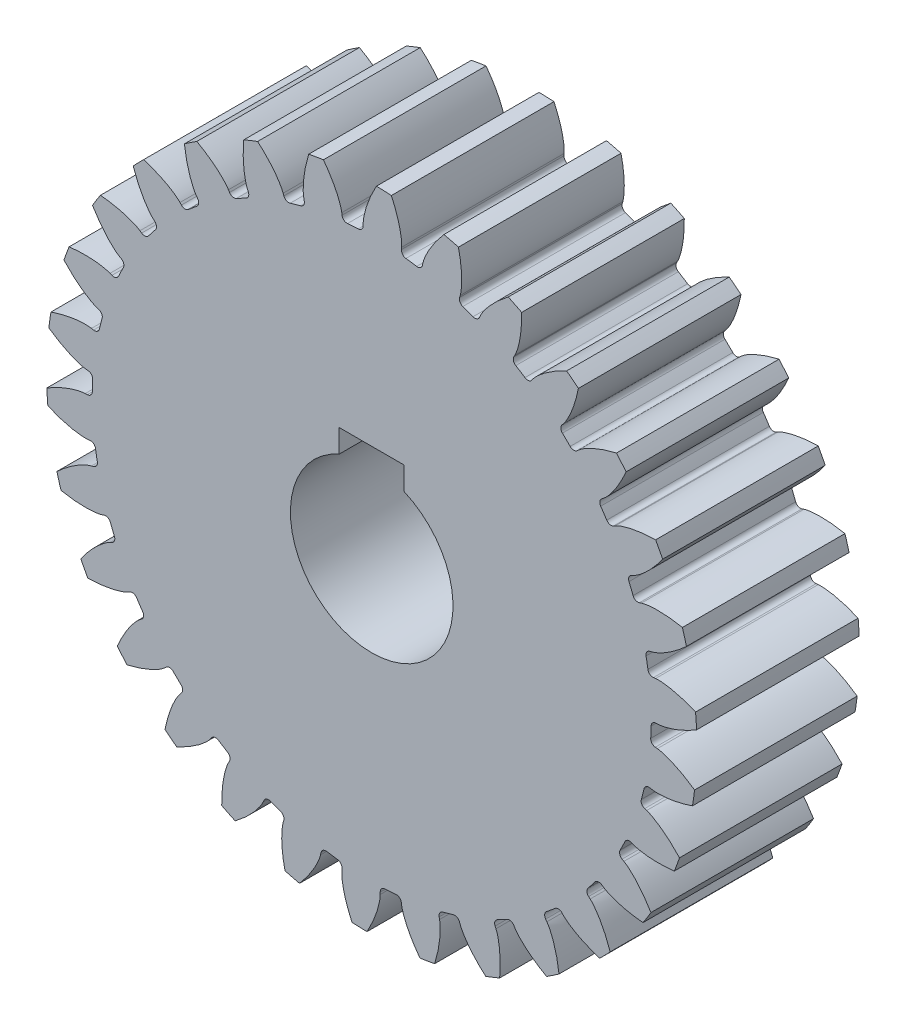
SolidWorks part; units mm, degrees
material "普通碳钢"
ref_plane "前视基准面" through (0, 0, 0) normal (0, 0, 1) x (1, 0, 0)
ref_plane "上视基准面" through (0, 0, 0) normal (0, 1, 0) x (1, 0, 0)
ref_plane "右视基准面" through (0, 0, 0) normal (1, 0, 0) x (0, 0, -1)
sketch "草图1" plane through (0, 0, 0) normal (0, 0, 1) x (1, 0, 0)
  circle A0 centre (0, 0) radius 40
  circle A1 centre (0, 0) radius 35.2385 construction
  spline S0 degree 4 poles (35.2385, 0) (35.2645, 0.0006) (35.3375, 0.0038) (35.4753, 0.0167) (35.6991, 0.0472) (35.9825, 0.1001) (36.3462, 0.1844) (36.7705, 0.304) (37.2317, 0.4565) (37.7271, 0.6449) (38.2153, 0.8527) (38.6956, 1.0778) (39.1683, 1.3186) (39.7325, 1.6284) (40.3986, 2.0272) (41.1576, 2.5279) (41.9984, 3.1428) (42.8253, 3.8079) (43.6227, 4.5077) (44.3913, 5.2397) (45.0381, 5.9049) (45.5755, 6.4929) (46.0974, 7.0914) (46.523, 7.6039) (46.9323, 8.1186) (47.3374, 8.6535) (47.6437, 9.0696) (47.9643, 9.5236) (48.2398, 9.9227) (48.6343, 10.5199) (48.8641, 10.8815) (49.2267, 11.4659) (49.3796, 11.7307) (49.5219, 11.9693) (49.5614, 12.0402) (49.5915, 12.0919) (49.6078, 12.1198) knots 0 0 0 0 0 0.005377 0.015084 0.028532 0.04661 0.064855 0.092111 0.119476 0.146842 0.174209 0.201575 0.228941 0.256307 0.307035 0.361767 0.4165 0.471232 0.525964 0.580697 0.635429 0.662795 0.690161 0.744894 0.77226 0.799626 0.826992 0.854358 0.881725 0.909091 0.954545 0.977273 0.988636 0.994318 1 1 1 1 1 construction
  spline S1 degree 4 poles (35.2385, 0) (35.2645, 0.0006) (35.3375, 0.0038) (35.4753, 0.0167) (35.6991, 0.0472) (35.9825, 0.1001) (36.3462, 0.1844) (36.7705, 0.304) (37.2317, 0.4565) (37.7271, 0.6449) (38.2153, 0.8527) (38.6956, 1.0778) (39.1683, 1.3186) (39.7325, 1.6284) (40.3986, 2.0272) (41.1576, 2.5279) (41.9984, 3.1428) (42.8253, 3.8079) (43.6227, 4.5077) (44.3913, 5.2397) (45.0381, 5.9049) (45.5755, 6.4929) (46.0974, 7.0914) (46.523, 7.6039) (46.9323, 8.1186) (47.3374, 8.6535) (47.6437, 9.0696) (47.9643, 9.5236) (48.2398, 9.9227) (48.4937, 10.3071) (48.6265, 10.5113) (48.6916, 10.6127) knots 0 0 0 0 0 0.005377 0.015084 0.028532 0.04661 0.064855 0.092111 0.119476 0.146842 0.174209 0.201575 0.228941 0.256307 0.307035 0.361767 0.4165 0.471232 0.525964 0.580697 0.635429 0.662795 0.690161 0.744894 0.77226 0.799626 0.826992 0.854358 0.881725 0.909091 0.909091 0.909091 0.909091 0.909091 construction
  dimension "D1" = 80
  dimension "D2" = 70.4769
  dimension "D3" = 48.6916
extrude "凸台-拉伸1" add sketch "草图1" along normal blind 20
sketch "草图2" plane through (0, 0, 0) normal (0, 0, -1) x (-1, 0, 0)
  line L0 (0, 0) -> (-50000, 0) construction
  line L1 (0, 0) -> (-49994.4466, 745.1896) construction
  line L2 (0, 0) -> (-49960.2244, -1872.1625) construction
  line L3 (-35.2385, 0) -> (-34.375, -0.0182)
  line L4 (-35.1396, -2.6373) -> (-34.28, -2.5545)
  circle A0 centre (0, 0) radius 37.5 construction
  arc A1 (-34.375, -0.0182) -> (-34.28, -2.5545) centre (0, 0) ccw
  circle A2 centre (0, 0) radius 40 construction
  arc A3 (-39.9609, 1.7682) -> (-39.7165, -4.754) centre (0, 0) ccw
  spline S0 degree 4 poles (-26.9358, 1999.8706) (-29.3876, 36.783) (-31.5593, 0.6865) (-33.6591, -0.2313) (-35.6991, 0.0472) (-35.9825, 0.1001) (-36.3462, 0.1844) (-36.7705, 0.304) (-37.2317, 0.4565) (-37.7271, 0.6449) (-38.2153, 0.8527) (-38.6956, 1.0778) (-39.1683, 1.3186) (-39.7325, 1.6284) (-40.3986, 2.0272) (-41.1576, 2.5279) (-41.9984, 3.1428) (-42.8253, 3.8079) (-43.6227, 4.5077) (-44.3913, 5.2397) (-45.0381, 5.9049) (-45.5755, 6.4929) (-46.0974, 7.0914) (-46.523, 7.6039) (-46.9323, 8.1186) (-47.3374, 8.6535) (-47.6437, 9.0696) (-47.9643, 9.5236) (-49.3305, 11.5028) (-52.4953, 16.7376) (-16.2689, -39.0455) (-1128.4864, 1694.0178) knots -0.378218 -0.378218 -0.378218 -0.378218 -0.378218 0.005377 0.015084 0.028532 0.04661 0.064855 0.092111 0.119476 0.146842 0.174209 0.201575 0.228941 0.256307 0.307035 0.361767 0.4165 0.471232 0.525964 0.580697 0.635429 0.662795 0.690161 0.744894 0.77226 0.799626 0.826992 0.854358 0.881725 1.342522 1.342522 1.342522 1.342522 1.342522 only from (-35.2385, 0) to (-48.6916, 10.6127) construction
  spline S1 degree 4 poles (-35.2385, 0) (-35.2645, 0.0006) (-35.3375, 0.0038) (-35.4753, 0.0167) (-35.6991, 0.0472) (-35.9825, 0.1001) (-36.3462, 0.1844) (-36.7705, 0.304) (-37.2317, 0.4565) (-37.7271, 0.6449) (-38.2153, 0.8527) (-38.6956, 1.0778) (-39.1683, 1.3186) (-39.5424, 1.524) (-39.7971, 1.6711) (-39.936, 1.7534) (-39.9609, 1.7682) knots 0 0 0 0 0 0.005377 0.015084 0.028532 0.04661 0.064855 0.092111 0.119476 0.146842 0.174209 0.201575 0.228941 0.256307 0.262277 0.262277 0.262277 0.262277 0.262277
  spline S2 degree 4 poles (-35.1396, -2.6373) (-35.1656, -2.6398) (-35.2381, -2.6485) (-35.3745, -2.6716) (-35.5954, -2.7189) (-35.8741, -2.7928) (-36.2305, -2.9041) (-36.6446, -3.055) (-37.0932, -3.2417) (-37.5731, -3.4666) (-38.0443, -3.7103) (-38.5064, -3.9708) (-38.9598, -4.2463) (-39.3174, -4.4791) (-39.5604, -4.6449) (-39.6928, -4.7374) (-39.7165, -4.754) knots 0 0 0 0 0 0.005377 0.015084 0.028532 0.04661 0.064855 0.092111 0.119476 0.146842 0.174209 0.201575 0.228941 0.256307 0.262277 0.262277 0.262277 0.262277 0.262277
  point P3 (-37.4958, 0.5589)
  dimension "D1" = 75
  dimension "D2" = 68.75
  dimension "D3" = 3
extrude "切除-拉伸1" cut sketch "草图2" against normal through all
fillet "圆角1" radius 0.625 2 edges at (34.28, -2.5545, 10) (34.375, -0.0182, 10)
pattern_circular "阵列(圆周)1" count 30 over 360 about axis through (0, 0, 20) along (0, 0, -1) of "切除-拉伸1", "圆角1"
sketch "草图3" plane through (0, 0, 0) normal (0, 0, -1) x (-1, 0, 0)
  line L0 (-4, 9.1652) -> (-4, 12)
  line L1 (-4, 12) -> (4, 12)
  line L2 (4, 12) -> (4, 9.1652)
  line L3 (0, 0) -> (50000, 0) construction
  line L4 (0, 0) -> (0, -50000) construction
  arc A0 (-4, 9.1652) -> (4, 9.1652) centre (0, 0) ccw
  dimension "D1" = 20
  dimension "D2" = 8
  dimension "D3" = 12
extrude "切除-拉伸2" cut sketch "草图3" against normal through all
equation "\"M\"= 2.5"
equation "\"Z\"= 30"
equation "\"a\"= 20"
equation "\"r\"= \"M\" * \"Z\" * cos ( \"a\" ) / 2"
equation "\"ha\"= 1"
equation "\"c\"= 0.25"
equation "\"x\"= 0"
equation "\"D1@草图1\"= \"M\" * ( \"Z\" + \"ha\" + \"ha\" + \"x\" + \"x\" ) "
equation "\"D2@草图1\"= \"r\" * 2 "
equation "\"D3@草图1\" = \"r\" * ( cos ( 180 / pi ) +  sin ( 180 / pi  ) )"
equation "\"D1@草图2\"= \"M\" * \"Z\" "
equation "\"D2@草图2\"= \"M\" * ( \"Z\" - \"ha\" - \"ha\" - \"c\" - \"c\" + \"x\" + \"x\" ) "
equation "\"D3@草图2\"= 90 / \"Z\""
equation "\"D1@圆角1\" = \"M\" / 4"
equation "\"D1@阵列(圆周)1\" = \"Z\""
